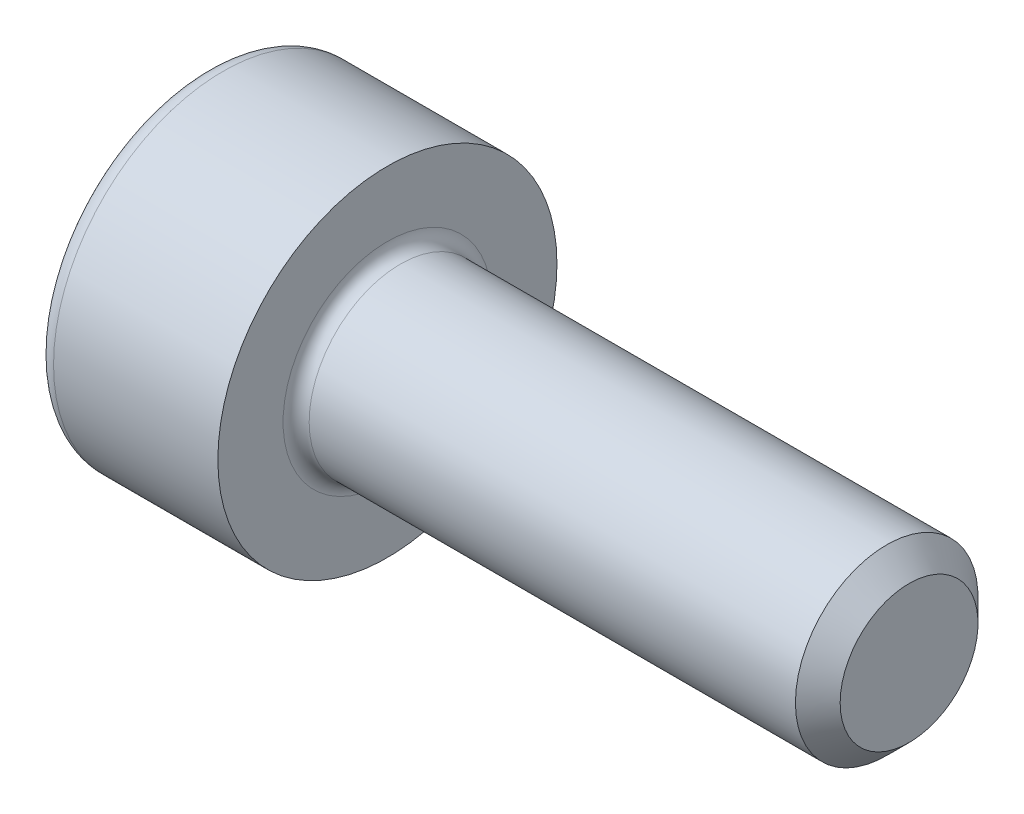
SolidWorks part; units mm, degrees
revolve "Base-Revolve" add sketch "BodySke"
sketch "BodySke" plane through (0, 0, 0) normal (0, 0, 1) x (1, 0, 0)
  line L0 (0, 0) -> (0, 1.3)
  line L1 (0, 1.3) -> (1.4, 1.3)
  line L2 (1.4, 1.3) -> (1.4, 0.7)
  line L3 (1.4, 0.7) -> (5.2285, 0.7)
  line L4 (5.4, 0.5285) -> (5.4, 0)
  line L5 (5.4, 0) -> (0, 0)
  line L6 (-31.75, 0) -> (127, 0) construction
  line L8 (5.4, 0.5285) -> (5.2285, 0.7)
  line L10 (5.4, -0.5285) -> (5.2285, -0.7) construction
  line L11 (1.7, 9.525) -> (1.7, 3.175) construction
  line L12 (1.4, 9.525) -> (1.4, 3.175) construction
  line L13 (-54.6, 9.525) -> (-54.6, 3.175) construction
  dimension "Head_ht" = 1.4
  dimension "Length" = 4
  dimension "Body_ch_ang" = 45
  dimension "Diameter" = 1.4
  dimension "Minor_dia" = 1.057
  dimension "Advance" = 0.3
  dimension "Thread_nom" = 4
  dimension "Thread_length" = 60
  dimension "Head_dia" = 2.6
cosmetic thread "ThreadCosmetic" [suppressed]
fillet "Fillet1" radius 0.1 1 edges at (1.4, 0, 0.7)
fillet "Fillet2" radius 0.14 1 edges at (0, 0, 1.3)
ref_plane "Plane1" through (0, 0, 0) normal (0, 0, 1) x (1, 0, 0)
ref_plane "Plane2" through (0, 0, 0) normal (0, 1, 0) x (1, 0, 0)
ref_plane "Plane3" through (0, 0, 0) normal (1, 0, 0) x (0, 0, -1)
sketch "Sketch2" plane through (0, 0, 0) normal (0, 0, 1) x (1, 0, 0)
  line L0 (0, 0.66) -> (0.6, 0.66)
  line L1 (0.6, 0.66) -> (0.9811, 0)
  line L2 (-31.75, 0) -> (127, 0) construction
  line L3 (0.9811, 0) -> (0, 0)
  line L4 (0, 0) -> (0, 0.66)
  line L6 (0, 0) -> (47.625, 0) construction
  dimension "D1" = 0.66
  dimension "D2" = 60
  dimension "Depth" = 0.6
revolve "Hex-PreBroach" cut sketch "Sketch2" angle 360 about L6
sketch "Sketch3" plane through (0, 0, 0) normal (-1, 0, 0) x (0, 0.5, 0.866)
  line L0 (0.3811, 0.66) -> (-0.3811, 0.66)
  line L1 (-0.3811, 0.66) -> (-0.7621, 0)
  line L2 (0.3811, 0.66) -> (0.7621, 0)
  line L3 (0.3811, -0.66) -> (0.7621, 0)
  line L4 (0.3811, -0.66) -> (-0.3811, -0.66)
  line L5 (-0.3811, -0.66) -> (-0.7621, 0)
  dimension "D1" = 0.66
  dimension "D2" = 0.66
  dimension "Hex_size" = 1.32
extrude "Hex" cut sketch "Sketch3" against normal blind 0.6
sketch "ThdSchSke" plane through (0, 0, 0) normal (0, 0, 1) x (1, 0, 0)
  line L0 (2.3, -0.5285) -> (2.1799, -0.7)
  line L1 (2.3, -0.5285) -> (2.4201, -0.7)
  line L2 (2.4201, -0.7) -> (2.4201, -0.875)
  line L3 (-3.175, 0) -> (5.1513, 0) construction
  line L4 (0, 1.16) -> (0, -1.16) construction
  line L5 (2.4201, -0.875) -> (2.1799, -0.875)
  line L6 (2.1799, -0.875) -> (2.1799, -0.7)
  dimension "Thread_minor" = 1.057
  dimension "Diameter" = 1.4
  dimension "Start" = 2.3
revolve "ThreadSchematic" [suppressed] cut sketch "ThdSchSke" angle 360 about L3
pattern_linear "ThdSchPat" [suppressed]
equation "\"D2@Sketch3\" = \"Hex_size@Sketch3\" / 2"
equation "\"D1@Sketch3\" = \"Hex_size@Sketch3\" / 2"
equation "\"D1@Sketch2\" = \"Hex_size@Sketch3\" / 2"
equation "\"Thread_minor@ThreadCosmetic\"  =  \"Minor_dia@BodySke\""
equation "\"Depth@Sketch2\" =  \"Key_eng@Hex\""
equation "\"Thread_length@ThreadCosmetic\" = ((sgn( (\"Length@BodySke\" - \"Advance@BodySke\" * 3.0) - \"Thread_nom@BodySke\" )-1)*( (\"Length@BodySke\" - \"Advance@BodySke\" * 3.0) - \"Thread_nom@BodySke\" ))/-2+ \"Thread_nom@BodySke\""
equation "\"Thread_minor@ThdSchSke\" = \"Minor_dia@BodySke\""
equation "\"Diameter@ThdSchSke\" = \"Diameter@BodySke\""
equation "\"Overcut@ThdSchSke\" = \"Diameter@BodySke\" * 1.25"
equation "\"Start@ThdSchSke\" = \"Head_ht@BodySke\" + \"Length@BodySke\" - \"Thread_length@ThreadCosmetic\"  '---Non-countersunk---"
equation "\"Num_threads@ThdSchPat\" = int( \"Thread_length@ThreadCosmetic\" / \"Advance@BodySke\" + 0.999 )  + 1"
equation "\"Advance@ThdSchPat\" = \"Thread_length@ThreadCosmetic\" /  (\"Num_threads@ThdSchPat\" - 1) 'relax it"
equation "\"Num_threads@ThdSchPat\" = \"Num_threads@ThdSchPat\" - sgn( \"Num_threads@ThdSchPat\" - 1) '---chamfered tips only---"
